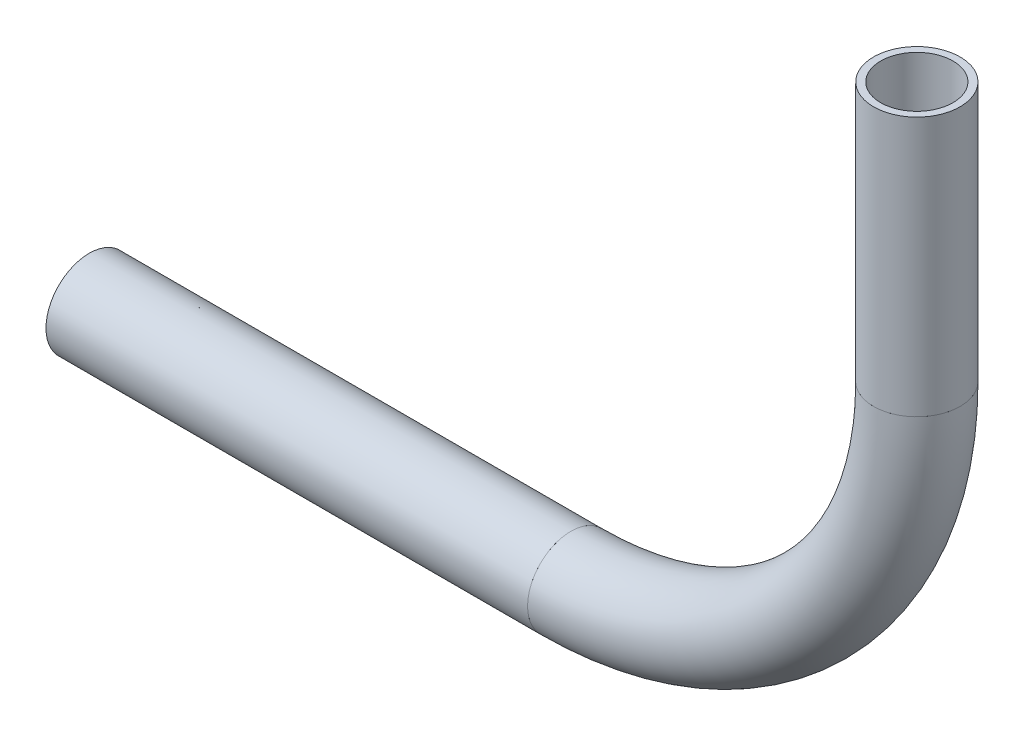
SolidWorks part; units mm, degrees
ref_plane "Front Plane" through (0, 0, 0) normal (0, 0, 1) x (1, 0, 0)
ref_plane "Top Plane" through (0, 0, 0) normal (0, 1, 0) x (1, 0, 0)
ref_plane "Right Plane" through (0, 0, 0) normal (1, 0, 0) x (0, 0, -1)
sketch "Sketch3" plane through (0, 0, 0) normal (0, 0, 1) x (1, 0, 0)
  line L0 (-669.0269, -788.6429) -> (-669.0269, -826.7429)
  line L1 (-719.8269, -877.5429) -> (-790.5373, -877.5429)
  arc A0 (-669.0269, -826.7429) -> (-719.8269, -877.5429) centre (-719.8269, -826.7429) cw
  dimension "D1" = 50.8
  dimension "D2" = 38.1
other "Pipe 0.5 SCH 40(1)"
ref_plane "Plane1" through (-669.0269, -826.7429, 0) normal (0, -1, 0) x (1, 0, 0)
sketch "Sketch1" plane through (-669.0269, -826.7429, 0) normal (0, -1, 0) x (1, 0, 0)
  circle A0 centre (0, 0) radius 5.3086
  circle A1 centre (0, 0) radius 6.35
  point P5 (0, 0)
  dimension "In_dia" = 10.6172
  dimension "Out_dia" = 12.7
